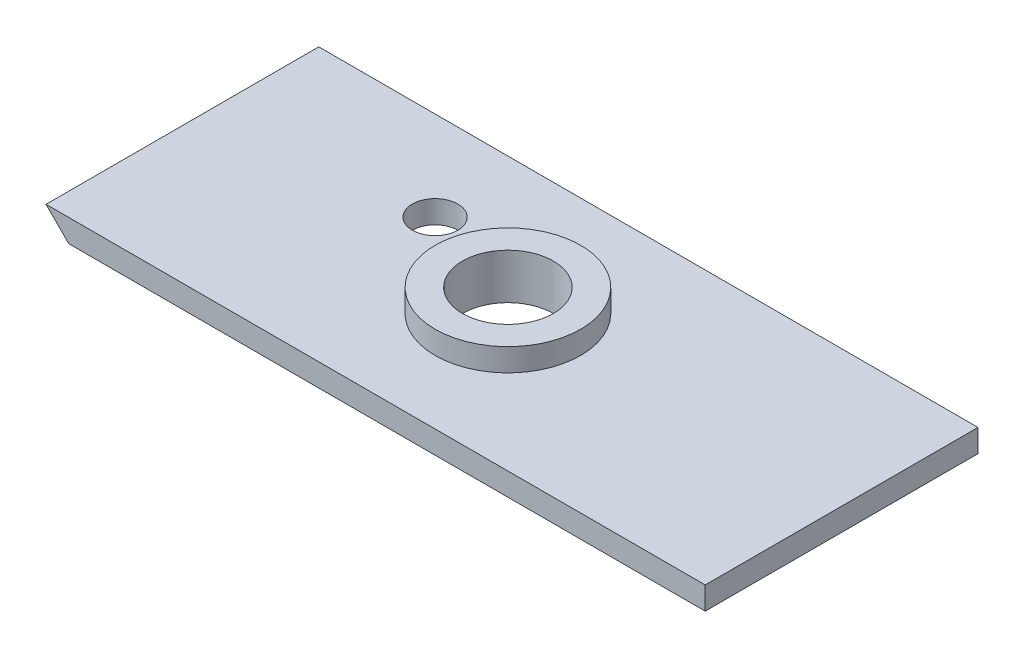
SolidWorks part; units mm, degrees
ref_plane "前视基准面" through (0, 0, 0) normal (0, 0, 1) x (1, 0, 0)
ref_plane "上视基准面" through (0, 0, 0) normal (0, 1, 0) x (1, 0, 0)
ref_plane "右视基准面" through (0, 0, 0) normal (1, 0, 0) x (0, 0, -1)
sketch "草图2" plane through (0, 0, 0) normal (0, 1, 0) x (1, 0, 0)
  line L0 (-21.1496, -1.9474) -> (21.7063, -1.9474) construction
  line L1 (-18.5276, 4.0526) -> (11.4724, 4.0526)
  line L2 (-18.5276, 4.0526) -> (-18.5276, -7.9474)
  line L3 (-18.5276, -7.9474) -> (11.4724, -7.9474)
  line L4 (11.4724, 4.0526) -> (11.4724, -7.9474)
  circle A1 centre (-5.2076, -1.9474) radius 2
  circle A2 centre (-5.2076, -1.9474) radius 3.2 construction
  dimension "D3" = 13.32
  dimension "D4" = 4
  dimension "D5" = 6.4
  dimension "D1" = 30
  dimension "D2" = 12
extrude "凸台-拉伸1" add sketch "草图2" along normal blind 1
sketch "草图3" plane through (0, 1, 0) normal (0, 1, 0) x (1, 0, 0)
  circle A0 centre (-5.2076, -1.9474) radius 2
  circle A1 centre (-5.2076, -1.9474) radius 3.2
extrude "凸台-拉伸2" add sketch "草图3" along normal blind 1
sketch "草图4" plane through (0, 0, 0) normal (0, -1, 0) x (1, 0, 0)
  line L0 (-18.5276, -4.0526) -> (-18.5276, 7.9474) construction
  line L6 (11.4724, -4.0526) -> (-18.5276, -4.0526) construction
  circle A0 centre (-10.4812, -0.1227) radius 1
  dimension "D1" = 8.0464
  dimension "D2" = 3.9299
extrude "切除-拉伸1" cut sketch "草图4" against normal blind 5
sketch "草图5" plane through (0, 0, -4.0526) normal (0, 0, -1) x (-1, 0, 0)
  line L0 (18.5276, 1) -> (18.5276, 0)
  line L1 (18.5276, 0) -> (19.5276, 1)
  line L2 (19.5276, 1) -> (18.5276, 1)
  dimension "D1" = 1
extrude "凸台-拉伸3" add sketch "草图5" against normal blind 12
sketch "草图6" plane through (0, 0, 0) normal (0, -1, 0) x (1, 0, 0)
  line L0 (11.4724, -4.0526) -> (-18.5276, -4.0526) construction
  line L1 (11.4724, 7.9474) -> (9.4724, 7.9474)
  line L2 (11.4724, 7.9474) -> (11.4724, -4.0526)
  line L3 (11.4724, -4.0526) -> (9.4724, -4.0526)
  line L4 (9.4724, 7.9474) -> (9.4724, -4.0526)
  dimension "D1" = 2
extrude "切除-拉伸2" cut sketch "草图6" against normal blind 1
